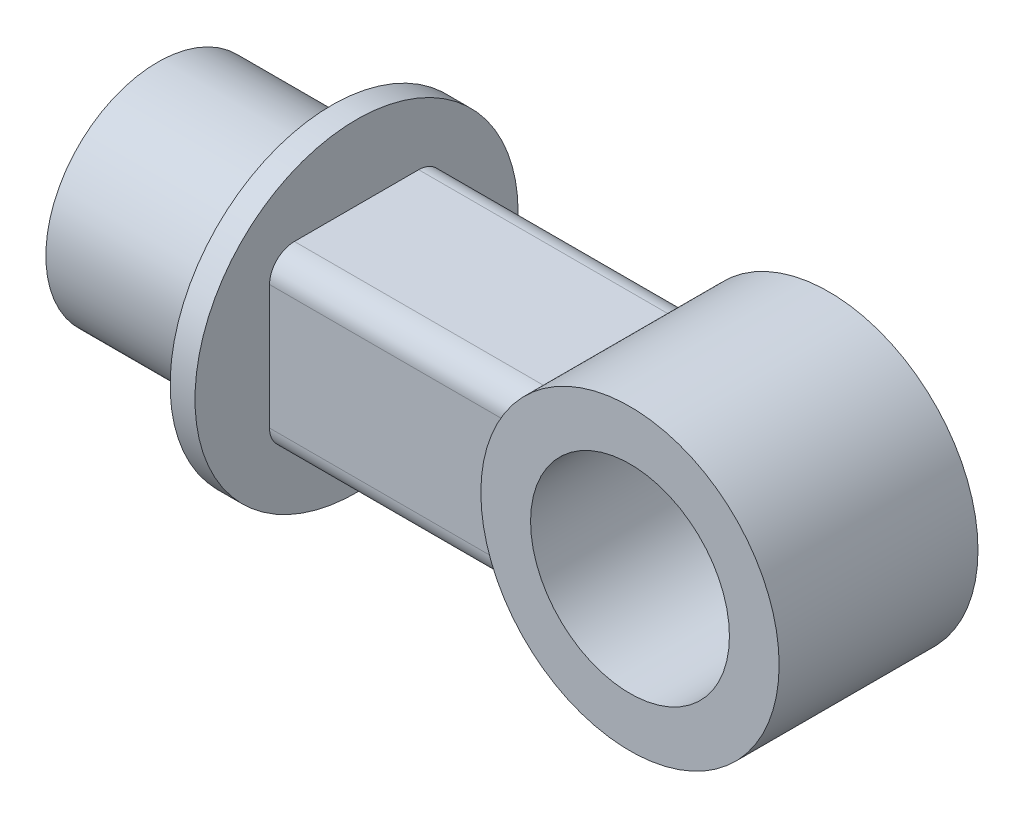
SolidWorks part; units mm, degrees
ref_plane "Front Plane" through (0, 0, 0) normal (0, 0, 1) x (1, 0, 0)
ref_plane "Top Plane" through (0, 0, 0) normal (0, 1, 0) x (1, 0, 0)
ref_plane "Right Plane" through (0, 0, 0) normal (1, 0, 0) x (0, 0, -1)
sketch "Sketch1" plane through (0, 0, 0) normal (1, 0, 0) x (0, 0, -1)
  circle A0 centre (0, 0) radius 45
  dimension "D1" = 90
extrude "Boss-Extrude1" add sketch "Sketch1" along normal blind 70
sketch "Sketch2" plane through (70, 0, 0) normal (1, 0, 0) x (0, 0, -1)
  circle A0 centre (0, 0) radius 65
  dimension "D1" = 130
extrude "Boss-Extrude2" add sketch "Sketch2" along normal blind 10
sketch "Sketch3" plane through (0, 0, 0) normal (0, 0, 1) x (1, 0, 0)
  line L0 (-4.838, 0) -> (230, 0) construction
  line L1 (80, -65) -> (80, 65) construction
  circle A0 centre (230, 0) radius 40
  circle A1 centre (230, 0) radius 60
  dimension "D1" = 80
  dimension "D2" = 120
  dimension "D3" = 150
extrude "Boss-Extrude3" add sketch "Sketch3" along normal mid plane 80 separate body
sketch "Sketch4" plane through (80, 0, 0) normal (1, 0, 0) x (0, 0, -1)
  line L1 (-35, 35) -> (35, 35)
  line L2 (-35, 35) -> (-35, -35)
  line L3 (-35, -35) -> (35, -35)
  line L4 (35, 35) -> (35, -35)
  line L5 (-35, 35) -> (35, -35) construction
  line L6 (-35, -35) -> (35, 35) construction
  point P0 (0, 0)
  dimension "D1" = 70
  dimension "D2" = 70
extrude "Boss-Extrude4" add sketch "Sketch4" along normal blind 110
fillet "Fillet1" radius 10 4 edges at (130.633, -35, 35) (130.633, -35, -35) (130.633, 35, 35) (130.633, 35, -35)
